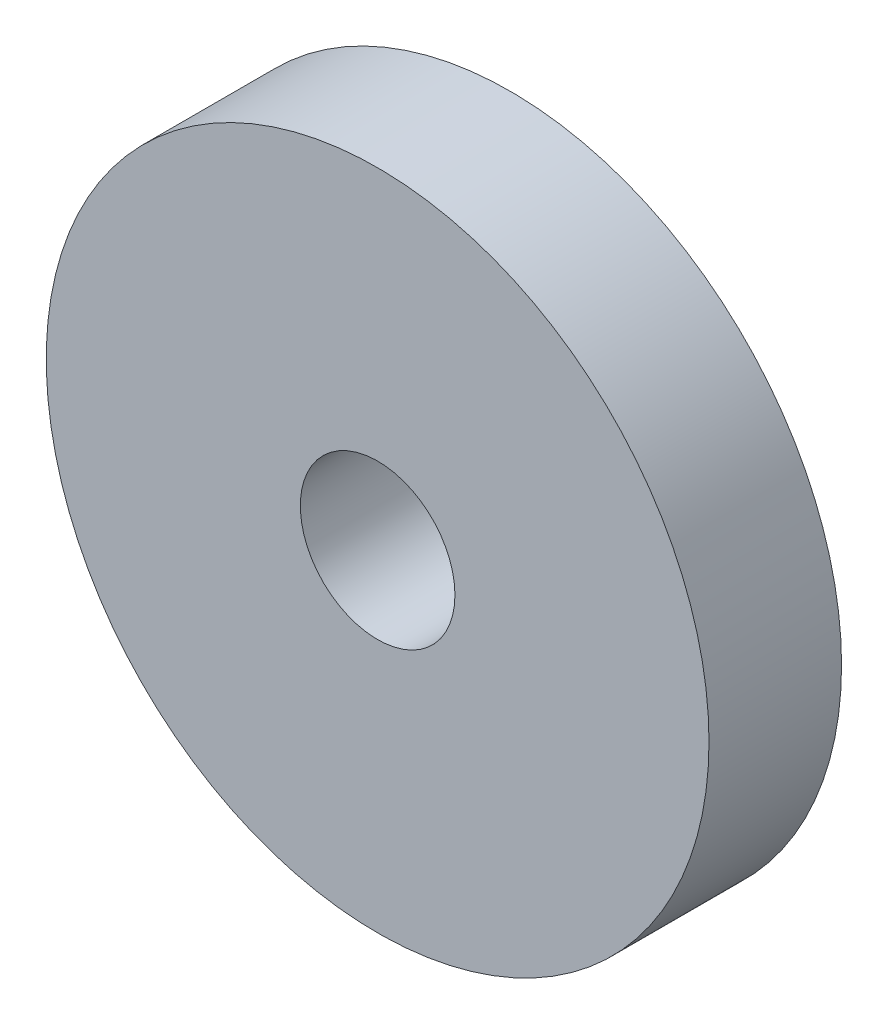
SolidWorks part; units mm, degrees
ref_plane "Front Plane" through (0, 0, 0) normal (0, 0, 1) x (1, 0, 0)
ref_plane "Top Plane" through (0, 0, 0) normal (0, 1, 0) x (1, 0, 0)
ref_plane "Right Plane" through (0, 0, 0) normal (1, 0, 0) x (0, 0, -1)
sketch "Sketch1" plane through (0, 0, 0) normal (0, 0, 1) x (1, 0, 0)
  circle A0 centre (0, 0) radius 7.5
  circle A1 centre (0, 0) radius 1.75
  dimension "D1" = 3.5
  dimension "D2" = 15
extrude "Boss-Extrude1" add sketch "Sketch1" along normal blind 3
